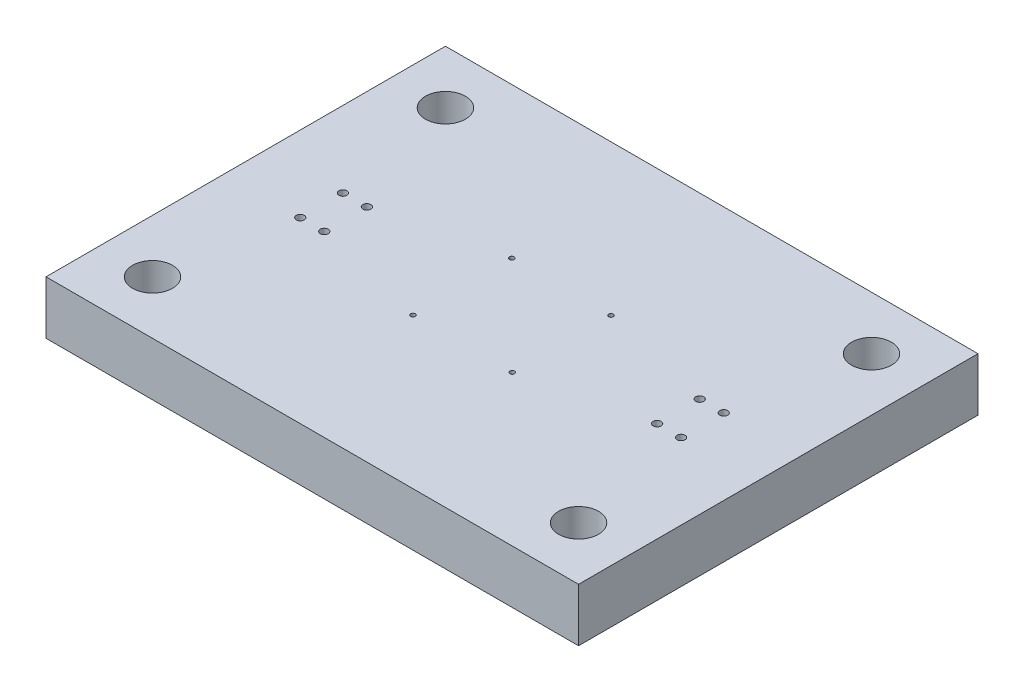
SolidWorks part; units mm, degrees
ref_plane "Front Plane" through (0, 0, 0) normal (0, 0, 1) x (1, 0, 0)
ref_plane "Top Plane" through (0, 0, 0) normal (0, 1, 0) x (1, 0, 0)
ref_plane "Right Plane" through (0, 0, 0) normal (1, 0, 0) x (0, 0, -1)
sketch "Sketch1" plane through (0, 0, 0) normal (0, 1, 0) x (1, 0, 0)
  line L1 (-100, 75) -> (100, 75)
  line L2 (-100, 75) -> (-100, -75)
  line L3 (-100, -75) -> (100, -75)
  line L4 (100, 75) -> (100, -75)
  line L5 (-100, 75) -> (100, -75) construction
  line L6 (-100, -75) -> (100, 75) construction
  point P0 (0, 0)
  dimension "D1" = 200
  dimension "D2" = 150
extrude "Boss-Extrude1" add sketch "Sketch1" along normal blind 20
sketch "Sketch2" plane through (0, 20, 0) normal (0, 1, 0) x (1, 0, 0)
  line L0 (0, -75) -> (0, 75) construction
  line L1 (100, 75) -> (-100, 75) construction
  line L2 (-100, 0) -> (100, 0) construction
  line L3 (100, -75) -> (100, 75) construction
  line L4 (-100, 75) -> (-100, -75) construction
  circle A0 centre (-80, 55) radius 7.5
  circle A1 centre (80, 55) radius 7.5
  circle A2 centre (-80, -55) radius 7.5
  circle A3 centre (80, -55) radius 7.5
  point P6 (0, 0)
  point P10 (0, 0)
  point P12 (0, 0)
  dimension "D1" = 15
  dimension "D3" = 20
  dimension "D2" = 20
extrude "Cut-Extrude1" cut sketch "Sketch2" against normal through all
sketch "Sketch3" plane through (0, 0, 0) normal (0, -1, 0) x (1, 0, 0)
  line L0 (0, -75) -> (0, 75) construction
  line L1 (-80, 55) -> (80, 55) construction
  line L2 (-80, 55) -> (-80, -55) construction
  line L3 (-80, -55) -> (80, -55) construction
  line L4 (80, 55) -> (80, -55) construction
  line L5 (-100, 75) -> (100, 75) construction
  line L6 (-100, 0) -> (100, 0) construction
  line L7 (100, 75) -> (100, -75) construction
  line L8 (-80, 13) -> (-54, 13) construction
  line L9 (-80, 13) -> (-80, -13) construction
  line L10 (-54, 13) -> (-54, -13) construction
  line L11 (-80, -13) -> (-54, -13) construction
  line L12 (-67, -13) -> (-67, 13) construction
  circle A1 centre (-71.5, 8) radius 1.5
  circle A2 centre (-62.5, 8) radius 1.5
  circle A3 centre (-62.5, -8) radius 1.5
  circle A4 centre (-71.5, -8) radius 1.5
  circle A5 centre (62.5, -8) radius 1.5
  circle A6 centre (71.5, -8) radius 1.5
  circle A7 centre (62.5, 8) radius 1.5
  circle A8 centre (71.5, 8) radius 1.5
  point P12 (0, 0)
  point P18 (0, 0)
  dimension "D4" = 3
  dimension "D6" = 5
  dimension "D1" = 26
  dimension "D2" = 26
  dimension "D3" = 13
  dimension "D5" = 8.5
extrude "Cut-Extrude2" cut sketch "Sketch3" against normal through all both and the other way through all
sketch "Sketch4" plane through (0, 20, 0) normal (0, 1, 0) x (1, 0, 0)
  line L0 (0, 0) -> (0, 75) construction
  line L1 (100, 75) -> (-100, 75) construction
  line L2 (0, 0) -> (100, 0) construction
  line L3 (100, -75) -> (100, 75) construction
  line L4 (0, 0) -> (-100, 0) construction
  line L5 (-100, 75) -> (-100, -75) construction
  line L6 (0, 0) -> (0, -75) construction
  line L7 (-100, -75) -> (100, -75) construction
  line L9 (-21.5, 21.5) -> (21.5, 21.5) construction
  line L10 (-21.5, 21.5) -> (-21.5, -21.5) construction
  line L11 (-21.5, -21.5) -> (21.5, -21.5) construction
  line L12 (21.5, 21.5) -> (21.5, -21.5) construction
  line L13 (-21.5, 21.5) -> (21.5, -21.5) construction
  line L14 (-21.5, -21.5) -> (21.5, 21.5) construction
  circle A0 centre (-18.63, 18.55) radius 0.875
  circle A1 centre (18.63, 18.55) radius 0.875
  circle A2 centre (-18.63, -18.55) radius 0.875
  circle A3 centre (18.63, -18.55) radius 0.875
  point P14 (0, 0)
  dimension "D3" = 1.75
  dimension "D5" = 2.95
  dimension "D1" = 43
  dimension "D2" = 43
  dimension "D4" = 2.87
extrude "Cut-Extrude3" cut sketch "Sketch4" against normal through all
